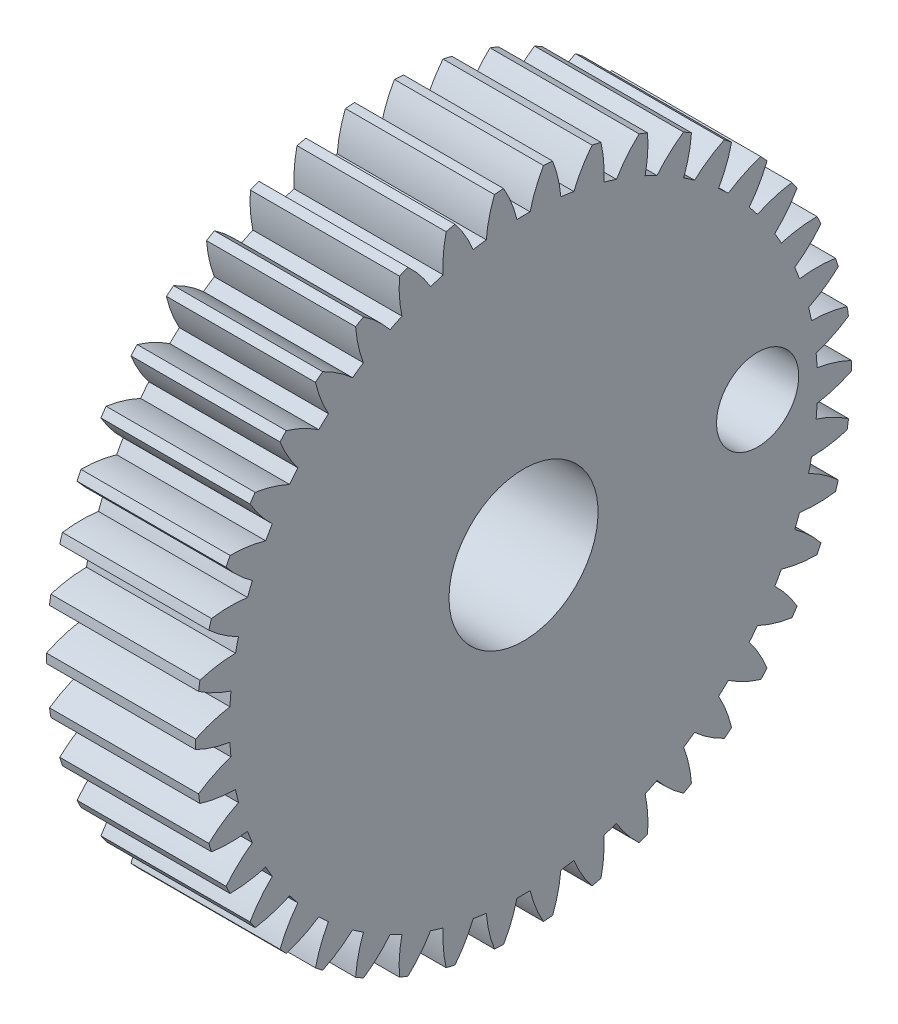
SolidWorks part; units mm, degrees
ref_plane "Plane1" through (0, 0, 0) normal (0, 0, 1) x (1, 0, 0)
ref_plane "Plane2" through (0, 0, 0) normal (0, 1, 0) x (1, 0, 0)
ref_plane "Plane3" through (0, 0, 0) normal (1, 0, 0) x (0, 0, -1)
sketch "HoldingSke" plane through (0, 0, 0) normal (0, 1, 0) x (1, 0, 0)
  line L0 (0, 0) -> (755.0351, -679.8367)
  line L1 (-15, 0) -> (100, 0) construction
  line L2 (0, 0) -> (-2.1039, 2.3779)
  line L3 (0, 0) -> (-11.863, 4.5341)
  line L4 (0, 0) -> (6.4178, 5.7786)
  line L5 (0, 0) -> (-47.5972, -17.7524)
  line L6 (0, 0) -> (-5.2639, -3.5516)
  line L7 (-2.1039, 2.3779) -> (8.8308, 51.9871)
  line L8 (-76.2, 54.61) -> (-69.596, 54.61)
  line L9 (-71.009, 38.7566) -> (-53.1078, 45.2721)
  line L10 (-76.2, 71.12) -> (104.1128, 71.12)
  line L11 (0, 0) -> (-6.35, 0)
  line L12 (-76.2, 101.6) -> (-76.1746, 101.6)
  line L13 (24.9733, 27.94) -> (52.9518, 28.4284)
  line L14 (24.9733, 27.94) -> (25.0241, 27.9398)
  line L15 (24.9733, 27.94) -> (100.4021, 29.52)
  circle A0 centre (0, 0) radius 3.175
  circle A1 centre (0, 0) radius 12.5222
  circle A2 centre (0, 0) radius 38.1
  circle A3 centre (0, 0) radius 3.175
  dimension "MHD" = 25.0444
  dimension "Hub_dia" = 76.2
  dimension "Bore" = 6.35
  dimension "MBD" = 6.35
  dimension "Num_teeth" = 42
  dimension "Pitch" = 1016
  dimension "Overall_len" = 50.8
  dimension "Show_teeth" = 42
  dimension "Thickness" = 6.35
  dimension "OAL" = 50.8001
  dimension "T_dim" = 6.604
  dimension "Ap" = 20
  dimension "H" = 19.05
  dimension "Pitch_radius" = 180.3128
  dimension "Width" = 6.35
  dimension "Backlash" = 0.0254
  dimension "Addendum_fac" = 1
  dimension "Dedendum_fac" = 1.2
  dimension "Clearance_fac" = 0.2
  dimension "Dedendum_add" = 0.0508
sketch "BasProSke" plane through (0, 0, 0) normal (0, 1, 0) x (1, 0, 0)
  line L0 (-10, 0) -> (60, 0) construction
  line L1 (0, 0) -> (0, 13.97)
  line L2 (0, 0) -> (6.35, 0)
  line L3 (6.35, 0) -> (6.35, 13.97)
  line L4 (6.35, 13.97) -> (0, 13.97)
  dimension "Thickness" = 6.35
  dimension "Diameter" = 27.94
revolve "Base-Revolve" add sketch "BasProSke" angle 360 about L0
sketch "TooCutSke" plane through (0, 0, 0) normal (1, 0, 0) x (0, 0, -1)
  line L1 (0, 0) -> (0, 107) construction
  line L2 (0, 0) -> (-0.5431, 13.3239) construction
  line L3 (0, 0) -> (-1.9919, 26.58) construction
  line L4 (-0.5431, 13.3239) -> (-0.9959, 13.29) construction
  arc A0 (0.2809, 12.519) -> (-0.2809, 12.519) centre (0, 0) ccw
  arc A1 (0.864, 13.9687) -> (-0.864, 13.9687) centre (0, 0) ccw
  circle A2 centre (0, 0) radius 13.335 construction
  circle A3 centre (0, 0) radius 12.5308 construction
  arc A4 (-0.2809, 12.519) -> (-0.864, 13.9687) centre (-5.4678, 11.2749) ccw
  arc A5 (0.864, 13.9687) -> (0.2809, 12.519) centre (5.4678, 11.2749) ccw
  dimension "Root_dia" = 25.0444
  dimension "Overcut_dia" = 27.9908
  dimension "Pitch_dia" = 26.67
  dimension "Base_dia" = 25.0616
  dimension "Flank_rad" = 5.334
  dimension "Half_ang" = 4.286
  dimension "Half_CT" = 0.4542
extrude "ToothCut" cut sketch "TooCutSke" along normal through all
fillet "Breaks" [suppressed] radius 0.0127
fillet "RootFillets" [suppressed] radius 0.1778
pattern_circular "TeethCuts" count 42 every 8.571 about axis through (-10, 0, 0) along (1, 0, 0) of "ToothCut", "RootFillets", "Breaks"
sketch "HubNeaOneSke" plane through (0, 0, 0) normal (-1, 0, 0) x (0, 0, 1)
  circle A0 centre (0, 0) radius 12.5222
  dimension "Diameter" = 25.0444
extrude "HubNearOne" [suppressed] add sketch "HubNeaOneSke" along normal blind 44.4501
sketch "HubNeaBotSke" plane through (0, 0, 0) normal (-1, 0, 0) x (0, 0, 1)
  circle A0 centre (0, 0) radius 12.5222
  dimension "Diameter" = 25.0444
extrude "HubNearBoth" [suppressed] add sketch "HubNeaBotSke" along normal blind 22.225
ref_plane "FarPln" through (6.35, 0, 0) normal (1, 0, 0) x (0, 0, -1)
sketch "HubFarSke" plane through (6.35, 0, 0) normal (1, 0, 0) x (0, 0, -1)
  circle A0 centre (0, 0) radius 12.5222
  dimension "Diameter" = 25.0444
extrude "HubFar" [suppressed] add sketch "HubFarSke" along normal blind 22.225
sketch "BorSke" plane through (0, 0, 0) normal (1, 0, 0) x (0, 0, -1)
  circle A0 centre (0, 0) radius 3.175
  dimension "Diameter" = 6.35
extrude "Bore" cut sketch "BorSke" along normal mid plane 101.6001
sketch "KeySke" plane through (0, 0, 0) normal (1, 0, 0) x (0, 0, -1)
  line L0 (-0.127, 0) -> (-0.127, 3.429)
  line L1 (-0.127, 3.429) -> (0.127, 3.429)
  line L2 (0.127, 3.429) -> (0.127, 0)
  line L3 (0, 0) -> (0, 34) construction
  line L4 (-0.127, 0) -> (0.127, 0)
  dimension "Offset" = 3.429
  dimension "Width" = 0.254
extrude "Keyway" [suppressed] cut sketch "KeySke" along normal mid plane 101.6001
pattern_circular "Keyway2" [suppressed] count 2 every 90 about axis through (-10, 0, 0) along (1, 0, 0)
sketch "Sketch1" plane through (6.35, 0, 0) normal (1, 0, 0) x (0, 0, -1)
  line L0 (0, 0) -> (9.972, 0.7473) construction
  line L1 (0, 0) -> (9.71, 0) construction
  line L2 (9.972, 0.7473) -> (12.4872, 0.9358) construction
  circle A0 centre (9.972, 0.7473) radius 1.75
  circle A1 centre (0, 0) radius 3.175 construction
  arc A3 (12.505, 0.6554) -> (12.463, 1.2157) centre (0, 0) ccw construction
  dimension "D2" = 3.5
  dimension "D1" = 10
extrude "Cut-Extrude1" cut sketch "Sketch1" against normal through all
equation "' \"Pitch@HoldingSke\" = 4"
equation "' \"Num_teeth@HoldingSke\" = 12"
equation "' \"Ap@HoldingSke\" =  20"
equation "' \"Ap@HoldingSke\" = 20"
equation "' \"Width@HoldingSke\" = 0.5"
equation "' \"Hub_dia@HoldingSke\"= 1"
equation "' \"Hub_dia@HoldingSke\" = 1"
equation "' \"Overall_len@HoldingSke\" = 1.0"
equation "' \"Bore@HoldingSke\" = 0.75"
equation "' \"T_dim@HoldingSke\" = 0.85"
equation "' \"Width@KeySke\" = 0.25"
equation "' \"Show_teeth@HoldingSke\" = 13"
equation "' \"Backlash@HoldingSke\" = 0.009"
equation "' \"Addendum_fac@HoldingSke\" = 1.0"
equation "' \"Dedendum_fac@HoldingSke\" = 1.25"
equation "' \"Dedendum_add@HoldingSke\" = 0.00005"
equation "' \"Clearance_fac@HoldingSke\" = 0.25"
equation "' \"Pitch@HoldingSke\" = 0.5"
equation "' \"Num_teeth@HoldingSke\" = 23"
equation "' \"Show_teeth@HoldingSke\" = 23"
equation "' \"Backlash@HoldingSke\" = 0.0375"
equation "\"Overcut_dia@TooCutSke\" = (\"Num_teeth@HoldingSke\" + 2 * \"Addendum_fac@HoldingSke\") / \"Pitch@HoldingSke\" + 0.002"
equation "\"Pitch_dia@TooCutSke\" = \"Num_teeth@HoldingSke\" / \"Pitch@HoldingSke\""
equation "\"Base_dia@TooCutSke\" = \"Num_teeth@HoldingSke\" / \"Pitch@HoldingSke\" * cos((\"Ap@HoldingSke\"  * 3.14159265 / 180))"
equation "\"Root_dia@TooCutSke\" = (\"Num_teeth@HoldingSke\" + 2) / \"Pitch@HoldingSke\" - 2 * (\"Addendum_fac@HoldingSke\" + \"Dedendum_fac@HoldingSke\") / \"Pitch@HoldingSke\" - \"Dedendum_add@HoldingSke\" * 2"
equation "\"Half_ang@TooCutSke\" = 180 / \"Num_teeth@HoldingSke\""
equation "\"Half_CT@TooCutSke\" = \"Num_teeth@HoldingSke\" / \"Pitch@HoldingSke\" * sin((3.14159265 / 2 / \"Num_teeth@HoldingSke\")) / 2 - 7 * \"Backlash@HoldingSke\" / 4"
equation "\"Flank_rad@TooCutSke\" = \"Num_teeth@HoldingSke\" / \"Pitch@HoldingSke\" / 5"
equation "\"Radius@RootFillets\" = \"Clearance_fac@HoldingSke\" / \"Pitch@HoldingSke\" + \"Dedendum_add@HoldingSke\""
equation "\"Break_rad@Breaks\" = 0.02 / \"Pitch@HoldingSke\""
equation "\"Thickness@HoldingSke\" = \"Width@HoldingSke\""
equation "\"OAL@HoldingSke\" = \"Thickness@HoldingSke\""
equation "\"MHD@HoldingSke\" = (\"Num_teeth@HoldingSke\" + 2) / \"Pitch@HoldingSke\" - 2 * (\"Addendum_fac@HoldingSke\" + \"Dedendum_fac@HoldingSke\")  / \"Pitch@HoldingSke\" - \"Dedendum_add@HoldingSke\" * 2"
equation "\"MBD@HoldingSke\" = (\"Num_teeth@HoldingSke\" + 2) / \"Pitch@HoldingSke\" - 2 * (\"Addendum_fac@HoldingSke\" + \"Dedendum_fac@HoldingSke\")  / \"Pitch@HoldingSke\" - \"Dedendum_add@HoldingSke\" * 2 - 0.002"
equation "\"MHD@HoldingSke\" = ((sgn( \"MHD@HoldingSke\" - \"Hub_dia@HoldingSke\" )-1)*( \"MHD@HoldingSke\" - \"Hub_dia@HoldingSke\" ))/-2+ \"Hub_dia@HoldingSke\""
equation "\"MBD@HoldingSke\" = ((sgn( \"MBD@HoldingSke\" - \"Bore@HoldingSke\" )-1)*( \"MBD@HoldingSke\" - \"Bore@HoldingSke\" ))/-2+ \"Bore@HoldingSke\""
equation "\"OAL@HoldingSke\" = ((sgn( \"OAL@HoldingSke\" - \"Overall_len@HoldingSke\" )+1)*( \"OAL@HoldingSke\" - \"Overall_len@HoldingSke\" ))/2 + \"Overall_len@HoldingSke\" + 0.000002"
equation "\"Num_teeth@TeethCuts\" = int( \"Show_teeth@HoldingSke\" ) + 1"
equation "\"Num_teeth@TeethCuts\" = ((sgn( \"Num_teeth@TeethCuts\" - \"Num_teeth@HoldingSke\" )-1)*( \"Num_teeth@TeethCuts\" - \"Num_teeth@HoldingSke\" ))/-2+ \"Num_teeth@HoldingSke\""
equation "\"Num_teeth@TeethCuts\" = ((sgn( \"Num_teeth@TeethCuts\" - 2.0)+1)*( \"Num_teeth@TeethCuts\" - 2.0))/2 +2.0"
equation "\"Angle@TeethCuts\" = 360.0 / \"Num_teeth@HoldingSke\""
equation "\"Diameter@BasProSke\" = (\"Num_teeth@HoldingSke\" + 2 * \"Addendum_fac@HoldingSke\") / \"Pitch@HoldingSke\""
equation "\"Thickness@BasProSke\"  = \"Thickness@HoldingSke\""
equation "' \"Fillet_rad@BasProSke\" =  \"Thickness@HoldingSke\" * 0.05"
equation "' \"Fillet_rad@BasProSke\" = \"Thickness@HoldingSke\" * 0.05"
equation "\"MHD@HoldingSke\" = ((sgn( \"MHD@HoldingSke\" - \"Root_dia@TooCutSke\" )-1)*( \"MHD@HoldingSke\" - \"Root_dia@TooCutSke\" ))/-2+ \"Root_dia@TooCutSke\""
equation "\"Diameter@HubNeaOneSke\" = \"MHD@HoldingSke\""
equation "\"Length@HubNearOne\" = \"OAL@HoldingSke\" - \"Thickness@BasProSke\""
equation "\"Diameter@HubNeaBotSke\" = \"MHD@HoldingSke\""
equation "\"Length@HubNearBoth\" = ( \"OAL@HoldingSke\" - \"Thickness@BasProSke\" ) / 2.0"
equation "\"Thickness@FarPln\" = \"Thickness@BasProSke\""
equation "\"Diameter@HubFarSke\" = \"MHD@HoldingSke\""
equation "\"Length@HubFar\" = ( \"OAL@HoldingSke\" - \"Thickness@BasProSke\" ) / 2.0"
equation "\"Diameter@BorSke\" = \"MBD@HoldingSke\""
equation "\"D1@Bore\" = \"OAL@HoldingSke\" * 2.0"
equation "\"D1@Keyway\" = \"OAL@HoldingSke\" * 2.0"
equation "\"Offset@KeySke\" = \"T_dim@HoldingSke\" - \"MBD@HoldingSke\" / 2.0"
